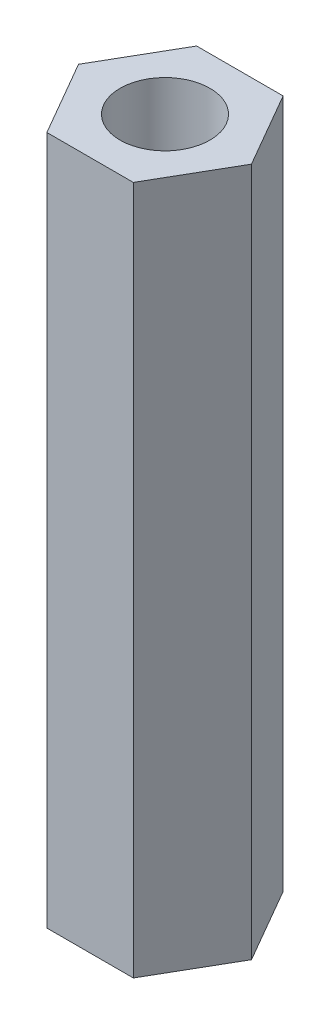
SolidWorks part; units mm, degrees
material "Laiton"
ref_plane "Plan de face" through (0, 0, 0) normal (0, 0, 1) x (1, 0, 0)
ref_plane "Plan de dessus" through (0, 0, 0) normal (0, 1, 0) x (1, 0, 0)
ref_plane "Plan de droite" through (0, 0, 0) normal (1, 0, 0) x (0, 0, -1)
sketch "Esquisse1" plane through (0, 0, 0) normal (0, 1, 0) x (1, 0, 0)
  line L1 (2.8868, 0) -> (1.4434, 2.5)
  line L2 (1.4434, 2.5) -> (-1.4434, 2.5)
  line L3 (-1.4434, 2.5) -> (-2.8868, 0)
  line L4 (-2.8868, 0) -> (-1.4434, -2.5)
  line L5 (-1.4434, -2.5) -> (1.4434, -2.5)
  line L6 (1.4434, -2.5) -> (2.8868, 0)
  circle A0 centre (0, 0) radius 2.5 construction
  circle A1 centre (0, 0) radius 1.5
  dimension "D1" = 5
  dimension "D2" = 3
extrude "Extrusion1" add sketch "Esquisse1" along normal blind 23
